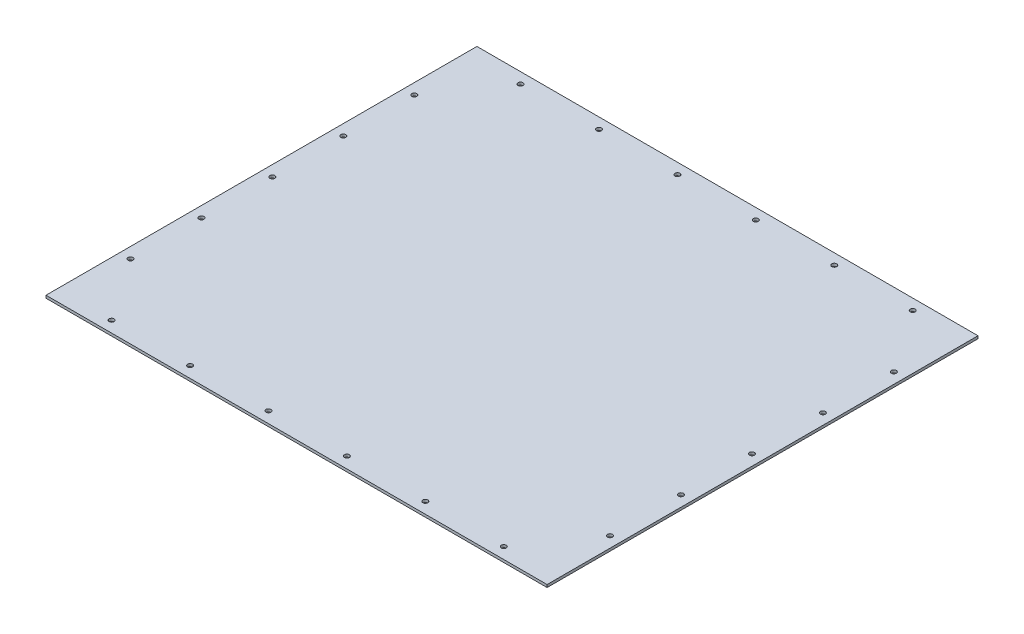
SolidWorks part; units mm, degrees
material "Acrylic (Medium-high impact)"
ref_plane "Front Plane" through (0, 0, 0) normal (0, 0, 1) x (1, 0, 0)
ref_plane "Top Plane" through (0, 0, 0) normal (0, 1, 0) x (1, 0, 0)
ref_plane "Right Plane" through (0, 0, 0) normal (1, 0, 0) x (0, 0, -1)
sketch "Sketch1" plane through (0, 0, 0) normal (0, 1, 0) x (1, 0, 0)
  line L1 (-292.1, 251.1933) -> (292.1, 251.1933)
  line L2 (-292.1, 251.1933) -> (-292.1, -251.1933)
  line L3 (-292.1, -251.1933) -> (292.1, -251.1933)
  line L4 (292.1, 251.1933) -> (292.1, -251.1933)
  line L5 (-292.1, 251.1933) -> (292.1, -251.1933) construction
  line L6 (-292.1, -251.1933) -> (292.1, 251.1933) construction
  point P0 (0, 0)
  dimension "D1" = 584.2
  dimension "D2" = 502.3866
extrude "TopPlate" add sketch "Sketch1" along normal blind 3.0734
sketch "Sketch2" plane through (0, 3.0734, 0) normal (0, 1, 0) x (1, 0, 0)
  line L0 (-228.6, 238.5949) -> (-292.1, 238.5949) construction
  line L1 (-292.1, 251.1933) -> (-292.1, -251.1933) construction
  line L2 (-228.6, 251.1933) -> (-228.6, 248.1199) construction
  line L3 (292.1, 251.1933) -> (-292.1, 251.1933) construction
  line L4 (-228.6, 248.1199) -> (-228.6, 229.0699) construction
  line L5 (-228.6, -238.2083) -> (-228.6, 238.5949) construction
  line L7 (-228.6, -247.7333) -> (-228.6, -250.7333) construction
  line L8 (-228.6, -250.7333) -> (-228.6, -253.7333) construction
  line L9 (-228.6, -247.7333) -> (-228.6, -228.6833) construction
  line L10 (-228.6, -253.7333) -> (-228.6, -256.8067) construction
  circle A0 centre (-228.6, 238.5949) radius 2.8956
  circle A1 centre (-228.6, -238.2083) radius 2.8956
  dimension "D2" = 5.7912
  dimension "D1" = 63.5
  dimension "D3" = 19.05
  dimension "D4" = 3.0734
  dimension "D5" = 19.05
  dimension "D6" = 3
  dimension "D7" = 3.0734
  dimension "D8" = 508
extrude "Front/RearTopHoles" cut sketch "Sketch2" against normal through all
pattern_linear "LPattern1" count 6 spacing 91.44 along (1, 0, 0) of "Front/RearTopHoles"
sketch "Sketch3" plane through (0, 3.0734, 0) normal (0, 1, 0) x (1, 0, 0)
  line L0 (-292.1, 165.6715) -> (-289.0266, 165.6715) construction
  line L1 (-292.1, 251.1933) -> (-292.1, -251.1933) construction
  line L2 (-289.0266, 165.6715) -> (-269.9766, 165.6715) construction
  line L3 (292.1, 251.1933) -> (-292.1, 251.1933) construction
  line L4 (292.1, 165.6715) -> (289.0266, 165.6715) construction
  line L5 (292.1, -251.1933) -> (292.1, 251.1933) construction
  line L6 (289.0266, 165.6715) -> (269.9766, 165.6715) construction
  line L7 (-279.5016, 251.1933) -> (-279.5016, 248.1199) construction
  line L8 (-279.5016, 248.1199) -> (-279.5016, 229.0699) construction
  circle A0 centre (-279.5016, 165.6715) radius 2.8956
  circle A1 centre (279.5016, 165.6715) radius 2.8956
  dimension "D3" = 19.05
  dimension "D1" = 5.7912
  dimension "D2" = 3.0734
  dimension "D5" = 3.0734
  dimension "D6" = 19.05
  dimension "D4" = 63.3984
extrude "Cut-Extrude2" cut sketch "Sketch3" against normal through all
pattern_linear "LPattern2" count 5 spacing 82.7391 along (0, 0, 1) of "Cut-Extrude2"
equation "\"Height\"= 32in"
equation "\"Width\"= 23in"
equation "\"Depth\"= 20in"
equation "\"Plexi\"= .121in"
equation "\"Boxsize\" = .75in"
equation "\"Boxinner\" = .625in"
equation "\"CornerCube\" = 0.75in"
equation "\"Cutwidth\"= .016in"
equation "\"Earsize\"= 1in + \"Cutwidth\" /2"
equation "\"Slotsize\" = 1in - \"CutWidth\" / 2"
equation "\"InnerWidth\" = \"Width\" - 2* \"Plexi\""
equation "\"InnerHeight\" = \"Height\" -2 * \"Plexi\""
equation "\"InnerDepth\" = \"Depth\" - 2*\"Plexi\""
equation "\"RearNumHoles\" = 7"
equation "\"RearHolesBorder\" = 2.2"
equation "\"RearHoleSpacing\" = (\"Width\" - 2*\"RearHolesBorder\") / (\"RearNumHoles\"-1)"
equation "\"RearBarLength\" = (\"InnerWidth\"-2*\"CornerCube\")"
equation "\"RearTopNumHoles\" = 6"
equation "\"RearTopHolesBorder\" = 2.5"
equation "\"RearTopHolesSpacing\" = (\"Width\" - 2*\"RearTopHolesBorder\") / (\"RearTopNumHoles\"-1)"
equation "\"SideVertNumHoles\" = 6"
equation "\"SideVertHolesBorder\" = \"CornerCube\"+\"FingerLength\"+.9"
equation "\"SideVertHoleSpacing\" = (\"InnerHeight\" - 2*\"SideVertHolesBorder\") / (\"SideVertNumHoles\"-1)"
equation "\"RivetDia\" = .228in"
equation "\"SlotDepth\" = \"Plexi\" + 0.75in + .005in"
equation "\"SideSlotWidth\"   = \"Plexi\"+.005in"
equation "\"SidePanelVertSpacing\" = (\"Height\"-2*(1.75-\"Plexi\")) / 5"
equation "\"BottomPanelSideHoleSpacing\" = (\"InnerDepth\"-2*(1.75-\"Plexi\")) / 4"
equation "\"D1@Sketch1\"=\"Width\""
equation "\"D2@Sketch1\"=\"TopDepth\""
equation "\"FrontDoorGap\" = .1in"
equation "\"TopDepth\" = \"Depth\"-\"DoorPlexi\"-\"FrontDoorGap\""
equation "\"D1@Sketch2\"=\"RearTopHolesBorder\""
equation "\"D2@Sketch2\"=\"RivetDia\""
equation "\"D3@Sketch2\"=\"Boxsize\""
equation "\"D4@Sketch2\"=\"Plexi\""
equation "\"D5@Sketch2\"=\"Boxsize\""
equation "\"MagnetThickness\"=3mm"
equation "\"MagnetDiameter\"=12mm"
equation "\"D6@Sketch2\"=\"MagnetThickness\""
equation "\"DoorPlexi\" = \"Plexi\""
equation "\"D7@Sketch2\"=\"DoorPlexi\""
equation "\"D8@Sketch2\"=\"Depth\""
equation "\"D3@LPattern1\"=\"RearTopHolesSpacing\""
equation "\"D1@LPattern1\"=\"RearTopNumHoles\""
equation "\"D1@Sketch3\"=\"RivetDia\""
equation "\"D2@Sketch3\"=\"Plexi\""
equation "\"D3@Sketch3\"=\"Boxsize\""
equation "\"FingerLength\" = 1.125in"
equation "\"SideTopNumHoles\" = 5"
equation "\"SideTopHoleOffset\"=\"CornerCube\"+\"FingerLength\"+\"Plexi\"+.5"
equation "\"SideTopHoleSpacing\" = (\"TopBarDepth\"-2*\"SideTopHoleOffset\") / (\"SideTopNumHoles\"-1)"
equation "\"SideHorizNumHoles\" = 6"
equation "\"SideHorizHoleBorder\" = 2.25"
equation "\"SideHorizHoleSpacing\" = (\"TopBarDepth\"-2*\"SideHorizHoleBorder\") / (\"SideHorizNumHoles\"-1)"
equation "\"TopBarDepth\" = \"Depth\"-\"DoorPlexi\"-\"Plexi\"-2*\"MagnetThickness\"-2*\"CornerCube\""
equation "\"D4@Sketch3\"=\"SideTopHoleOffset\""
equation "\"D3@LPattern2\"=\"SideTopHoleSpacing\""
equation "\"D1@LPattern2\"=\"SideTopNumHoles\""
equation "\"D5@Sketch3\"=\"Plexi\""
equation "\"D6@Sketch3\"=\"CornerCube\""
equation "\"EBWidth\" = 9in"
equation "\"BasePlateThickness\" = 0.5in"
equation "\"BasePlateWidth\" = \"Width\"+\"EBWidth\"-2*\"Plexi\""
equation "\"BasePlateDepth\" = \"Depth\"-\"Plexi\"-\"DoorPlexi\""
equation "\"BoxsizeHalf\" = \"Boxsize\"/2"
equation "\"FingerWidth\" = .625in"
equation "\"SideVertBarLength\"=\"Height\"-\"BasePlateThickness\"-2*\"CornerCube\"-\"Plexi\""
equation "\"RearSideVertNumHoles\" = 7"
equation "\"RearSideVertHolesBorder\" = 2.5"
equation "\"RearSideVertHoleSpacing\" = (\"InnerHeight\" - 2*\"RearSideVertHolesBorder\") / (\"RearSideVertNumHoles\"-1)"
equation "\"CoolerDepth\" = 12in"
equation "\"ShelfGap\" = 0.5in"
equation "\"ShelfDepth\" = \"TopBarDepth\"+\"CornerCube\"-\"CoolerDepth\""
equation "\"ShelfBarDepth\"=\"ShelfDepth\"-2*\"CornerCube\""
equation "\"ShelfWidth\" = \"EBWidth\"-\"ShelfGap\""
equation "\"ShelfBarWidth\" = \"EBWidth\"-\"Boxsize\""
equation "\"ShelfBarWidthShort\" = \"ShelfBarWidth\"-\"Boxsize\"-\"ShelfGap\""
equation "\"IntakeWidth\"=4in"
equation "\"IntakeHeight\"=2in"
equation "\"ExhaustWidth\"=4in"
equation "\"ExhaustHeight\"=2in"
equation "\"VentSpacing\"=7in"
equation "\"AngleBracketLength\"=20mm"
equation "\"AngleBracketWidth\"=10mm"
equation "\"AngleBracketThickness\"=1.5mm"
equation "\"AngleBracketHolePos\"=15mm"
equation "\"AngleBracketHoleDia\"=\"RivetDia\""
equation "\"ShelfBarAngleHole\"=\"ShelfGap\"+\"Boxsize\"+\"AngleBracketHolePos\""
equation "\"D1@TopPlate\"=\"Plexi\""
